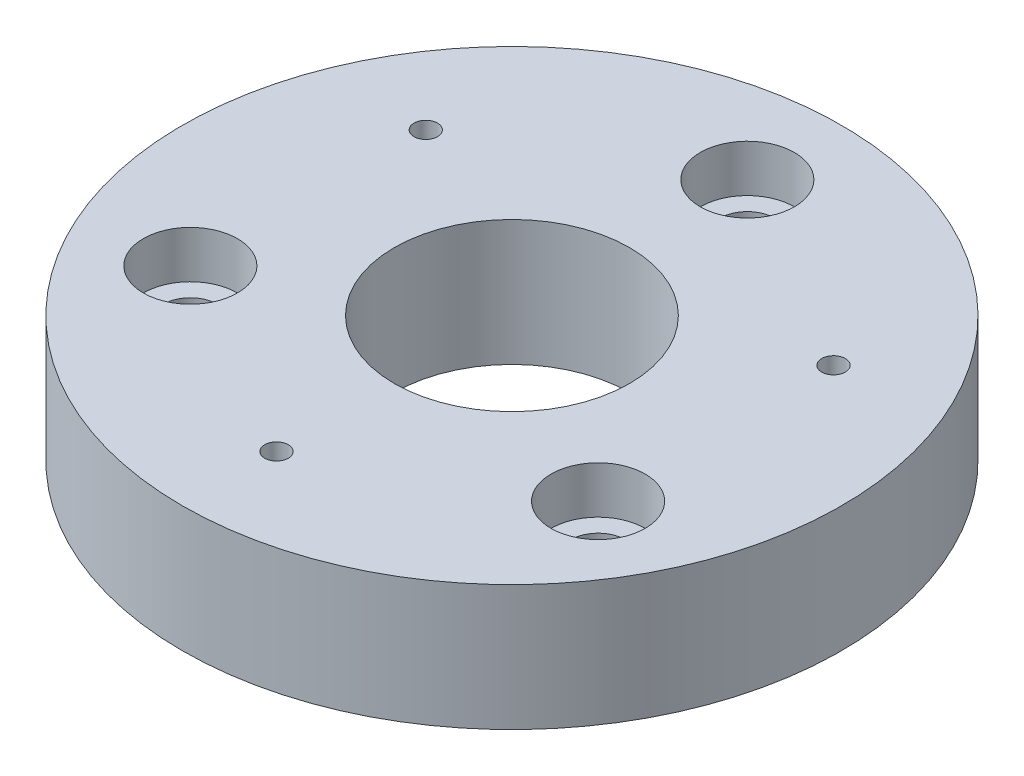
SolidWorks part; units mm, degrees
ref_plane "Front Plane" through (0, 0, 0) normal (0, 0, 1) x (1, 0, 0)
ref_plane "Top Plane" through (0, 0, 0) normal (0, 1, 0) x (1, 0, 0)
ref_plane "Right Plane" through (0, 0, 0) normal (1, 0, 0) x (0, 0, -1)
sketch "Sketch1" plane through (0, 0, 0) normal (0, 1, 0) x (1, 0, 0)
  circle A0 centre (0, 0) radius 21
  circle A1 centre (0, 0) radius 15 construction
  circle A2 centre (0, 15) radius 1.75
  circle A4 centre (0, -15) radius 0.75
  circle A6 centre (12.9904, -7.5) radius 1.75
  circle A7 centre (-12.9904, -7.5) radius 1.75
  circle A8 centre (-12.9904, 7.5) radius 0.75
  circle A9 centre (12.9904, 7.5) radius 0.75
  circle A10 centre (0, 0) radius 7.5
  dimension "D1" = 42
  dimension "D2" = 30
  dimension "D3" = 3.5
  dimension "D4" = 1.5
  dimension "D7" = 15
  dimension "D5" = 3
  dimension "D6" = 3
extrude "Boss-Extrude1" add sketch "Sketch1" along normal blind 8
sketch "Sketch2" plane through (0, 8, 0) normal (0, 1, 0) x (1, 0, 0)
  circle A0 centre (0, 15) radius 3
  circle A1 centre (12.9904, -7.5) radius 3
  circle A2 centre (-12.9904, -7.5) radius 3
  dimension "D1" = 6
  dimension "D2" = 3
extrude "Cut-Extrude1" cut sketch "Sketch2" against normal blind 3
